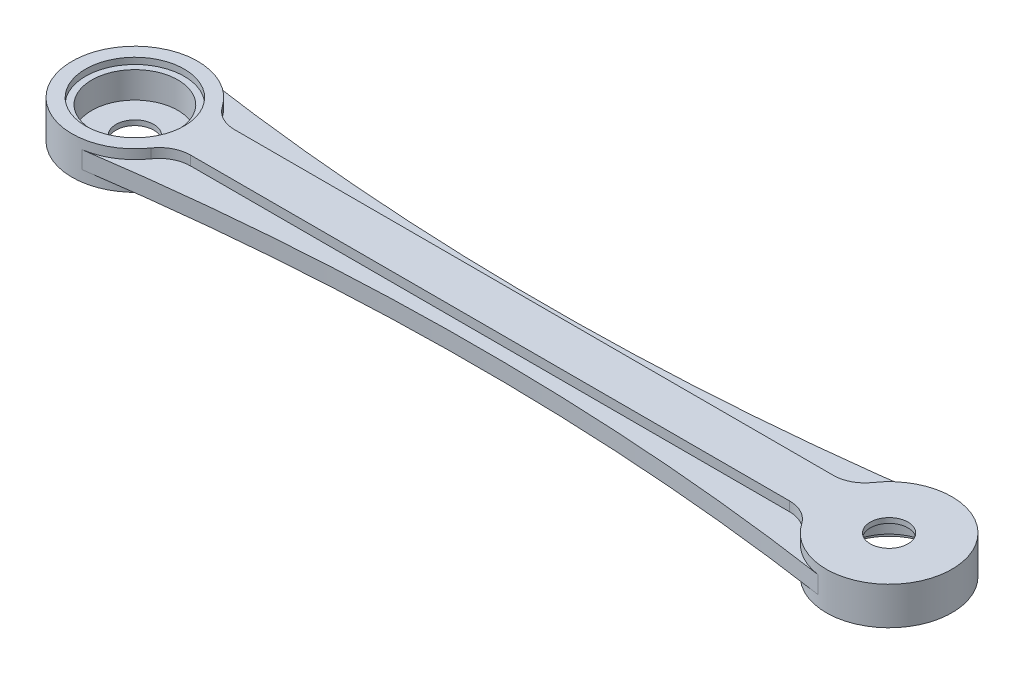
SolidWorks part; units mm, degrees
ref_plane "Front" through (0, 0, 0) normal (0, 0, 1) x (1, 0, 0)
ref_plane "Top" through (0, 0, 0) normal (0, 1, 0) x (1, 0, 0)
ref_plane "Right" through (0, 0, 0) normal (1, 0, 0) x (0, 0, -1)
sketch "Sketch1" plane through (0, 0, 0) normal (0, 1, 0) x (1, 0, 0)
  line L0 (0, 59.3117) -> (0, -50.1338) construction
  line L1 (-140.8795, 0) -> (95.6788, 0) construction
  circle A0 centre (0, 0) radius 7.85
  circle A1 centre (-120, 0) radius 7.85
  circle A2 centre (0, 0) radius 10
  circle A3 centre (-120, 0) radius 10
  arc A4 (-118.5366, 9.8923) -> (0, 10.1116) centre (-60, 405.586) ccw
  arc A5 (-118.5366, -9.8923) -> (0, -10.1116) centre (-60, -405.586) cw
  circle A6 centre (-120, 0) radius 3
  circle A7 centre (0, 0) radius 3
  dimension "D1" = 120
  dimension "D2" = 20
  dimension "D3" = 15.7
  dimension "D4" = 15.7
  dimension "D5" = 20
  dimension "D6" = 400
extrude "Boss-Extrude3" add sketch "Sketch1" along normal blind 6 contours A1 A6 | A3 A1 | A3 A5 A2 A4 | A0 A7 | A2 A0
sketch "Sketch2" plane through (0, 6, 0) normal (0, 1, 0) x (1, 0, 0)
  circle A0 centre (-120, 0) radius 7.85 construction
  circle A1 centre (-120, 0) radius 7.85
extrude "Cut-Extrude1" cut sketch "Sketch2" against normal blind 1
sketch "Sketch3" plane through (0, 5, 0) normal (0, 1, 0) x (1, 0, 0)
  circle A0 centre (-120, 0) radius 6.85
extrude "Cut-Extrude2" cut sketch "Sketch3" against normal blind 4.2
sketch "Sketch4" plane through (0, 0, 0) normal (0, -1, 0) x (1, 0, 0)
  circle A0 centre (0, 0) radius 7.85 construction
  circle A1 centre (0, 0) radius 7.85
  arc A4 (-118.5366, 9.8923) -> (-118.5366, -9.8923) centre (-120, 0) ccw
  arc A5 (-1.4634, -9.8923) -> (-118.5366, -9.8923) centre (-60, -405.586) ccw
  arc A6 (-1.4634, -9.8923) -> (-1.4634, 9.8923) centre (0, 0) ccw
  arc A7 (-118.5366, 9.8923) -> (-1.4634, 9.8923) centre (-60, 405.586) ccw
  arc A8 (-118.5366, 9.8923) -> (-118.5366, -9.8923) centre (-120, 0) ccw
  arc A9 (-1.4634, -9.8923) -> (-118.5366, -9.8923) centre (-60, -405.586) ccw
  arc A10 (-1.4634, -9.8923) -> (-1.4634, 9.8923) centre (0, 0) ccw
  arc A11 (-118.5366, 9.8923) -> (-1.4634, 9.8923) centre (-60, 405.586) ccw
  dimension "D1" = 0
sketch "Sketch5" plane through (0, 0, 0) normal (0, -1, 0) x (1, 0, 0)
  circle A0 centre (0, 0) radius 7.85 construction
  circle A1 centre (0, 0) radius 7.85
  circle A2 centre (0, 0) radius 7.85
  arc A4 (-118.5366, 9.8923) -> (-118.5366, -9.8923) centre (-120, 0) ccw
  arc A5 (-1.4634, -9.8923) -> (-118.5366, -9.8923) centre (-60, -405.586) ccw
  arc A6 (-1.4634, -9.8923) -> (-1.4634, 9.8923) centre (0, 0) ccw
  arc A7 (-118.5366, 9.8923) -> (-1.4634, 9.8923) centre (-60, 405.586) ccw
  arc A8 (-118.5366, 9.8923) -> (-118.5366, -9.8923) centre (-120, 0) ccw
  arc A9 (-1.4634, -9.8923) -> (-118.5366, -9.8923) centre (-60, -405.586) ccw
  arc A10 (-1.4634, -9.8923) -> (-1.4634, 9.8923) centre (0, 0) ccw
  arc A11 (-118.5366, 9.8923) -> (-1.4634, 9.8923) centre (-60, 405.586) ccw
  circle M11 centre (0, 0) radius 3
  dimension "D1" = 0
extrude "Cut-Extrude3" cut sketch "Sketch5" against normal blind 1 contours A1 M11
sketch "Sketch6" plane through (0, 1, 0) normal (0, -1, 0) x (1, 0, 0)
  circle A0 centre (0, 0) radius 6.85
extrude "Cut-Extrude4" cut sketch "Sketch6" against normal blind 4.2
sketch "Sketch7" plane through (0, 0, 0) normal (0, -1, 0) x (1, 0, 0)
  line L0 (0, -59.3117) -> (0, 50.1338) construction
  line L1 (-140.8795, 0) -> (95.6788, 0) construction
  line L2 (0, -59.3117) -> (0, 50.1338)
  line L3 (-140.8795, 0) -> (95.6788, 0)
  line L4 (-107.6408, 3.5) -> (-12.3592, 3.5)
  line L5 (-107.6408, -3.5) -> (-12.3592, -3.5)
  circle A0 centre (0, 0) radius 7.85 construction
  circle A1 centre (0, 0) radius 10 construction
  circle A3 centre (-120, 0) radius 10 construction
  arc A4 (-118.5366, 9.8923) -> (-118.5366, -9.8923) centre (-120, 0) ccw
  arc A5 (-1.4634, -9.8923) -> (-118.5366, -9.8923) centre (-60, -405.586) ccw
  arc A6 (-1.4634, -9.8923) -> (-1.4634, 9.8923) centre (0, 0) ccw
  arc A7 (-118.5366, 9.8923) -> (-1.4634, 9.8923) centre (-60, 405.586) ccw
  arc A8 (-118.5366, 9.8923) -> (-118.5366, -9.8923) centre (-120, 0) ccw
  arc A9 (-1.4634, -9.8923) -> (-118.5366, -9.8923) centre (-60, -405.586) ccw
  arc A10 (-1.4634, -9.8923) -> (-1.4634, 9.8923) centre (0, 0) ccw
  arc A11 (-118.5366, 9.8923) -> (-1.4634, 9.8923) centre (-60, 405.586) ccw
  arc A12 (0, -7.85) -> (0, 7.85) centre (0, 0) ccw
  arc A13 (-8.2395, -5.6667) -> (-8.2395, 5.6667) centre (0, 0) ccw
  arc A15 (-111.7605, 5.6667) -> (-111.7605, -5.6667) centre (-120, 0) ccw
  arc A16 (-107.6408, 3.5) -> (-111.7605, 5.6667) centre (-107.6408, 8.5) cw
  arc A17 (-8.2395, 5.6667) -> (-12.3592, 3.5) centre (-12.3592, 8.5) cw
  arc A18 (-12.3592, -3.5) -> (-8.2395, -5.6667) centre (-12.3592, -8.5) cw
  arc A19 (-107.6408, -3.5) -> (-111.7605, -5.6667) centre (-107.6408, -8.5) ccw
  point P22 (-110.6325, 3.5)
  point P29 (-9.3675, 3.5)
  point P32 (-9.3675, -3.5)
  point P35 (-110.6325, -3.5)
  arc M18 (-118.5366, -9.8923) -> (-1.4634, -9.8923) centre (-60, -405.586) cw
  arc M20 (-1.4634, 9.8923) -> (-118.5366, 9.8923) centre (-60, 405.586) cw
  dimension "D3" = 5
  dimension "D4" = 5
  dimension "D2" = 7
  dimension "D1" = 0
extrude "Cut-Extrude5" cut sketch "Sketch7" against normal blind 1.5 contours A17 A13 A15 A16 L4 M20 | L5 A19 A15 A13 A18 M18
sketch "Sketch8" plane through (0, 6, 0) normal (0, 1, 0) x (1, 0, 0)
  line L0 (-107.6408, -3.5) -> (-12.3592, -3.5) construction
  line L1 (-107.6408, 3.5) -> (-12.3592, 3.5) construction
  line L2 (-107.6408, -3.5) -> (-12.3592, -3.5)
  line L3 (-107.6408, 3.5) -> (-12.3592, 3.5)
  arc A0 (-8.2395, -5.6667) -> (-8.2395, 5.6667) centre (0, 0) ccw construction
  arc A1 (-12.3592, 3.5) -> (-8.2395, 5.6667) centre (-12.3592, 8.5) ccw construction
  arc A2 (-8.2395, -5.6667) -> (-12.3592, -3.5) centre (-12.3592, -8.5) ccw construction
  arc A3 (-107.6408, -3.5) -> (-111.7605, -5.6667) centre (-107.6408, -8.5) ccw construction
  arc A4 (-111.7605, 5.6667) -> (-107.6408, 3.5) centre (-107.6408, 8.5) ccw construction
  arc A5 (-111.7605, 5.6667) -> (-111.7605, -5.6667) centre (-120, 0) ccw construction
  arc A6 (-118.5366, 9.8923) -> (-1.4634, 9.8923) centre (-60, 405.586) ccw construction
  arc A7 (-8.2395, -5.6667) -> (-8.2395, 5.6667) centre (0, 0) ccw
  arc A8 (-12.3592, 3.5) -> (-8.2395, 5.6667) centre (-12.3592, 8.5) ccw
  arc A9 (-8.2395, -5.6667) -> (-12.3592, -3.5) centre (-12.3592, -8.5) ccw
  arc A10 (-107.6408, -3.5) -> (-111.7605, -5.6667) centre (-107.6408, -8.5) ccw
  arc A11 (-111.7605, 5.6667) -> (-107.6408, 3.5) centre (-107.6408, 8.5) ccw
  arc A12 (-111.7605, 5.6667) -> (-111.7605, -5.6667) centre (-120, 0) ccw
  arc A13 (-118.5366, 9.8923) -> (-1.4634, 9.8923) centre (-60, 405.586) ccw
  arc M3 (-118.5366, -9.8923) -> (-1.4634, -9.8923) centre (-60, -405.586) cw
  arc M5 (-1.4634, 9.8923) -> (-118.5366, 9.8923) centre (-60, 405.586) cw
extrude "Cut-Extrude6" cut sketch "Sketch8" against normal blind 1.5 contours A12 A11 L3 A8 A7 M5 | A12 A7 A9 L2 A10 M3
sketch "Sketch9" plane through (0, 6, 0) normal (0, 1, 0) x (1, 0, 0)
  line L0 (-107.6408, 3.5) -> (-12.3592, 3.5) construction
  line L1 (-107.6408, 3.5) -> (-12.3592, 3.5)
  line L2 (-107.6408, -3.5) -> (-12.3592, -3.5) construction
  line L3 (-107.6408, -3.5) -> (-12.3592, -3.5)
  arc A0 (-8.2395, -5.6667) -> (-8.2395, 5.6667) centre (0, 0) ccw construction
  arc A1 (-8.2395, -5.6667) -> (-12.3592, -3.5) centre (-12.3592, -8.5) ccw construction
  arc A2 (-1.4634, -9.8923) -> (-118.5366, -9.8923) centre (-60, -405.586) ccw construction
  arc A3 (-118.5366, 9.8923) -> (-1.4634, 9.8923) centre (-60, 405.586) ccw construction
  arc A4 (-111.7605, 5.6667) -> (-111.7605, -5.6667) centre (-120, 0) ccw construction
  arc A5 (-111.7605, 5.6667) -> (-107.6408, 3.5) centre (-107.6408, 8.5) ccw construction
  arc A6 (-8.2395, -5.6667) -> (-8.2395, 5.6667) centre (0, 0) ccw
  arc A7 (-8.2395, -5.6667) -> (-12.3592, -3.5) centre (-12.3592, -8.5) ccw
  arc A8 (-1.4634, -9.8923) -> (-118.5366, -9.8923) centre (-60, -405.586) ccw
  arc A9 (-118.5366, 9.8923) -> (-1.4634, 9.8923) centre (-60, 405.586) ccw
  arc A10 (-111.7605, 5.6667) -> (-111.7605, -5.6667) centre (-120, 0) ccw
  arc A11 (-111.7605, 5.6667) -> (-107.6408, 3.5) centre (-107.6408, 8.5) ccw
  arc A12 (-12.3592, 3.5) -> (-8.2395, 5.6667) centre (-12.3592, 8.5) ccw construction
  arc A13 (-12.3592, 3.5) -> (-8.2395, 5.6667) centre (-12.3592, 8.5) ccw
  arc A14 (-107.6408, -3.5) -> (-111.7605, -5.6667) centre (-107.6408, -8.5) ccw construction
  arc A15 (-107.6408, -3.5) -> (-111.7605, -5.6667) centre (-107.6408, -8.5) ccw
sketch "Sketch10" plane through (0, 0, 0) normal (0, -1, 0) x (1, 0, 0)
  line L0 (-12.3592, -3.5) -> (-107.6408, -3.5) construction
  line L1 (-107.6408, 3.5) -> (-12.3592, 3.5) construction
  line L2 (-107.6408, -3.5) -> (-12.3592, -3.5)
  line L3 (-12.3592, 3.5) -> (-107.6408, 3.5)
  line L4 (-107.6408, -3.5) -> (-12.3592, -3.5)
  line L5 (-12.3592, 3.5) -> (-107.6408, 3.5)
  line L6 (-12.3592, -3.5) -> (-107.6408, -3.5)
  line L7 (-107.6408, 3.5) -> (-12.3592, 3.5)
  arc A0 (-107.6408, -3.5) -> (-111.7605, -5.6667) centre (-107.6408, -8.5) ccw construction
  arc A1 (-118.5366, -9.8923) -> (-111.7605, -5.6667) centre (-120, 0) ccw construction
  arc A2 (-1.4634, -9.8923) -> (-118.5366, -9.8923) centre (-60, -405.586) ccw construction
  arc A3 (-8.2395, -5.6667) -> (-1.4634, -9.8923) centre (0, 0) ccw construction
  arc A4 (-8.2395, -5.6667) -> (-12.3592, -3.5) centre (-12.3592, -8.5) ccw construction
  arc A5 (-12.3592, 3.5) -> (-8.2395, 5.6667) centre (-12.3592, 8.5) ccw construction
  arc A6 (-111.7605, 5.6667) -> (-107.6408, 3.5) centre (-107.6408, 8.5) ccw
  arc A7 (-111.7605, 5.6667) -> (-111.7605, -5.6667) centre (-120, 0) ccw
  arc A8 (-107.6408, -3.5) -> (-111.7605, -5.6667) centre (-107.6408, -8.5) ccw
  arc A9 (-8.2395, -5.6667) -> (-12.3592, -3.5) centre (-12.3592, -8.5) ccw
  arc A10 (-8.2395, -5.6667) -> (-8.2395, 5.6667) centre (0, 0) ccw
  arc A11 (-12.3592, 3.5) -> (-8.2395, 5.6667) centre (-12.3592, 8.5) ccw
  arc A12 (-111.7605, 5.6667) -> (-107.6408, 3.5) centre (-107.6408, 8.5) ccw
  arc A13 (-111.7605, 5.6667) -> (-111.7605, -5.6667) centre (-120, 0) ccw
  arc A14 (-107.6408, -3.5) -> (-111.7605, -5.6667) centre (-107.6408, -8.5) ccw
  arc A15 (-8.2395, -5.6667) -> (-12.3592, -3.5) centre (-12.3592, -8.5) ccw
  arc A16 (-8.2395, -5.6667) -> (-8.2395, 5.6667) centre (0, 0) ccw
  arc A17 (-12.3592, 3.5) -> (-8.2395, 5.6667) centre (-12.3592, 8.5) ccw
  arc A18 (-1.4634, 9.8923) -> (-8.2395, 5.6667) centre (0, 0) ccw construction
  arc A19 (-118.5366, 9.8923) -> (-1.4634, 9.8923) centre (-60, 405.586) ccw construction
  arc A20 (-111.7605, 5.6667) -> (-118.5366, 9.8923) centre (-120, 0) ccw construction
  arc A21 (-111.7605, 5.6667) -> (-107.6408, 3.5) centre (-107.6408, 8.5) ccw construction
  arc A22 (-107.6408, -3.5) -> (-111.7605, -5.6667) centre (-107.6408, -8.5) ccw
  arc A23 (-118.5366, -9.8923) -> (-111.7605, -5.6667) centre (-120, 0) ccw
  arc A24 (-1.4634, -9.8923) -> (-118.5366, -9.8923) centre (-60, -405.586) ccw
  arc A25 (-8.2395, -5.6667) -> (-1.4634, -9.8923) centre (0, 0) ccw
  arc A26 (-8.2395, -5.6667) -> (-12.3592, -3.5) centre (-12.3592, -8.5) ccw
  arc A27 (-12.3592, 3.5) -> (-8.2395, 5.6667) centre (-12.3592, 8.5) ccw
  arc A28 (-1.4634, 9.8923) -> (-8.2395, 5.6667) centre (0, 0) ccw
  arc A29 (-118.5366, 9.8923) -> (-1.4634, 9.8923) centre (-60, 405.586) ccw
  arc A30 (-111.7605, 5.6667) -> (-118.5366, 9.8923) centre (-120, 0) ccw
  arc A31 (-111.7605, 5.6667) -> (-107.6408, 3.5) centre (-107.6408, 8.5) ccw
  arc M11 (-107.6408, 3.5) -> (-111.7605, 5.6667) centre (-107.6408, 8.5) cw
  arc M12 (-111.7605, 5.6667) -> (-111.7605, -5.6667) centre (-120, 0) ccw
  arc M13 (-111.7605, -5.6667) -> (-107.6408, -3.5) centre (-107.6408, -8.5) cw
  line M14 (-107.6408, -3.5) -> (-12.3592, -3.5)
  arc M15 (-12.3592, -3.5) -> (-8.2395, -5.6667) centre (-12.3592, -8.5) cw
  arc M16 (-8.2395, -5.6667) -> (-8.2395, 5.6667) centre (0, 0) ccw
  arc M17 (-8.2395, 5.6667) -> (-12.3592, 3.5) centre (-12.3592, 8.5) cw
  line M18 (-12.3592, 3.5) -> (-107.6408, 3.5)
  dimension "D1" = 0
extrude "Cut-Extrude9" cut sketch "Sketch10" against normal blind 1.75 contours A29 M12 M11 M18 M17 M16 | A24 A13 M16 M15 M14 M13
